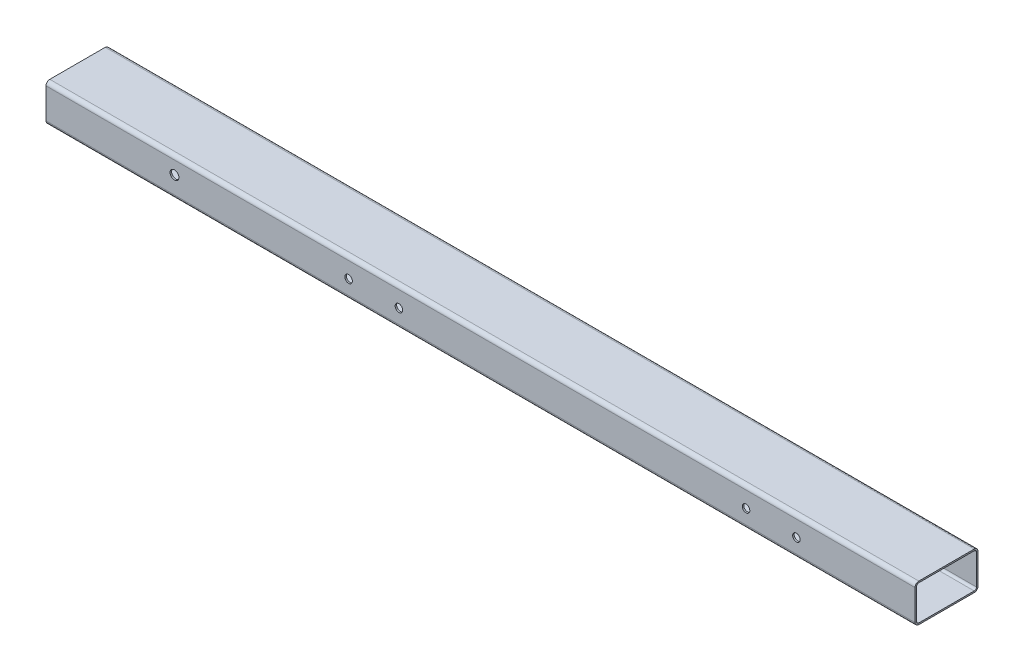
SolidWorks part; units mm, degrees
material "AISI 304"
ref_plane "Plano frontal" through (0, 0, 0) normal (0, 0, 1) x (1, 0, 0)
ref_plane "Plano superior" through (0, 0, 0) normal (0, 1, 0) x (1, 0, 0)
ref_plane "Plano direito" through (0, 0, 0) normal (1, 0, 0) x (0, 0, -1)
sketch "Esboço1" plane through (0, 0, 0) normal (0, 0, 1) x (1, 0, 0)
  line L0 (0, 0) -> (689.8, 0)
  dimension "D1" = 689.8
other "Tubo retangular 50 X 30 X 2.6(1)"
ref_plane "Plano1" through (0, 0, 0) normal (1, 0, 0) x (0, 1, 0)
sketch "Sketch1" plane through (0, 0, 0) normal (1, 0, 0) x (0, 1, 0)
  line L0 (-12, -23.8) -> (12, -23.8)
  line L1 (-13.8, -22) -> (-13.8, 22)
  line L2 (12, 23.8) -> (-12, 23.8)
  line L3 (13.8, 22) -> (13.8, -22)
  line L4 (-12, -25) -> (12, -25)
  line L5 (-15, -22) -> (-15, 22)
  line L6 (12, 25) -> (-12, 25)
  line L7 (15, 22) -> (15, -22)
  arc A0 (15, 22) -> (12, 25) centre (12, 22) ccw
  arc A1 (12, -25) -> (15, -22) centre (12, -22) ccw
  arc A2 (-15, -22) -> (-12, -25) centre (-12, -22) ccw
  arc A3 (-12, 25) -> (-15, 22) centre (-12, 22) ccw
  arc A4 (-12, 23.8) -> (-13.8, 22) centre (-12, 22) ccw
  arc A5 (13.8, 22) -> (12, 23.8) centre (12, 22) ccw
  arc A6 (12, -23.8) -> (13.8, -22) centre (12, -22) ccw
  arc A7 (-13.8, -22) -> (-12, -23.8) centre (-12, -22) ccw
  point P0 (0, 25)
  point P1 (15, 0)
  point P2 (0, -25)
  point P3 (-15, 0)
  point P4 (-15, 25)
  point P5 (15, 25)
  point P6 (15, -25)
  point P7 (-15, -25)
  point P8 (0, 0)
  point P33 (0, 0)
  dimension "D1" = 3
  dimension "Thickness" = 1.2
  dimension "V_leg" = 50
  dimension "H_leg" = 30
sketch "Esboço2" plane through (0, 0, -25) normal (0, 0, -1) x (-1, 0, 0)
  circle A0 centre (-55.1, -0.2) radius 1.8986
  circle A1 centre (-29.7, -0.2) radius 2.0828
  circle A2 centre (-4.3, -0.2) radius 1.8941
  circle A3 centre (-475.7, -0.2) radius 2.0828
  circle A4 centre (-450.3, -0.2) radius 1.8941
  circle A5 centre (-424.9, -0.2) radius 2.0828
extrude "Corte-extrusão1" [suppressed] cut sketch "Esboço2" against normal through all
sketch "Esboço4" plane through (0, 0, -25) normal (0, 0, -1) x (-1, 0, 0)
  circle A0 centre (-345, -0.5) radius 3.25
  circle A1 centre (-135, -0.5) radius 3.25
extrude "Corte-extrusão3" [suppressed] cut sketch "Esboço4" against normal through all
sketch "Esboço5" plane through (0, 0, 25) normal (0, 0, 1) x (1, 0, 0)
  circle A0 centre (280.1625, -0.653) radius 3
  circle A1 centre (240.1625, -0.653) radius 3
  circle A2 centre (595.6625, -0.653) radius 3
  circle A3 centre (555.6625, -0.653) radius 3
extrude "Corte-extrusão4" cut sketch "Esboço5" against normal through all
sketch "Esboço6" plane through (0, 0, 25) normal (0, 0, 1) x (1, 0, 0)
  circle A0 centre (102, 1.7694) radius 3.5
extrude "Corte-extrusão5" cut sketch "Esboço6" against normal through all
